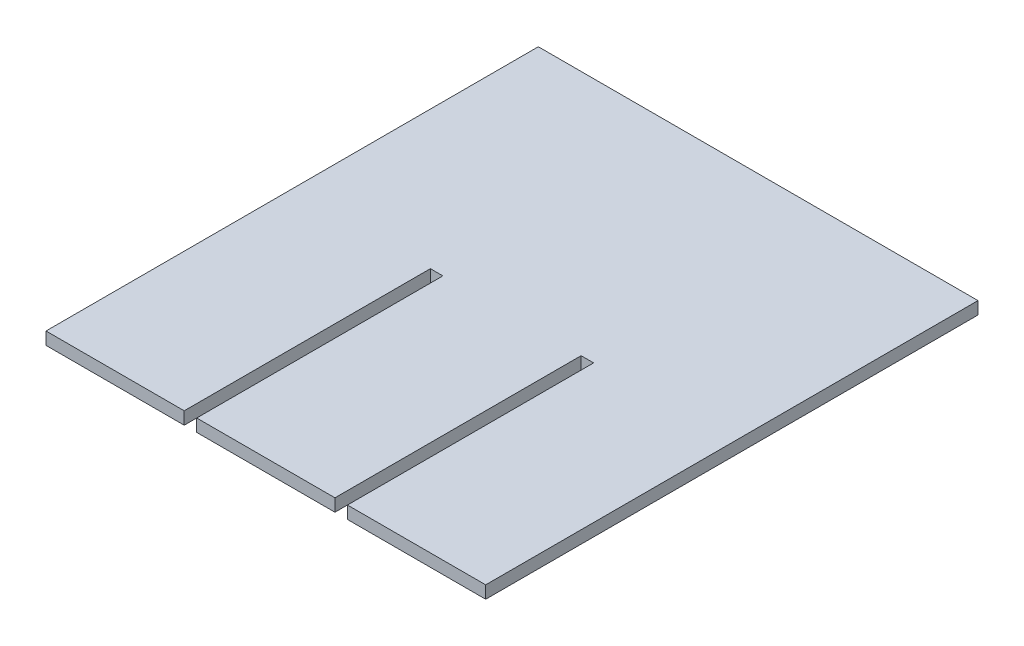
SolidWorks part; units mm, degrees
ref_plane "Front" through (0, 0, 0) normal (0, 0, 1) x (1, 0, 0)
ref_plane "Top" through (0, 0, 0) normal (0, 1, 0) x (1, 0, 0)
ref_plane "Right" through (0, 0, 0) normal (1, 0, 0) x (0, 0, -1)
sketch "Sketch1" plane through (0, 0, 0) normal (0, 1, 0) x (1, 0, 0)
  line L0 (0, 187.5) -> (105.2833, 187.5) construction
  line L1 (0, 0) -> (334.9, 0)
  line L2 (0, 0) -> (0, 375)
  line L3 (0, 375) -> (334.9, 375)
  line L4 (334.9, 0) -> (334.9, 375)
  line L5 (105.2833, 187.5) -> (114.8083, 187.5) construction
  line L6 (114.8083, 187.5) -> (220.0917, 187.5) construction
  line L7 (220.0917, 187.5) -> (229.6167, 187.5) construction
  line L8 (229.6167, 187.5) -> (334.9, 187.5) construction
  line L9 (105.2833, 0) -> (105.2833, 187.5)
  line L10 (105.2833, 187.5) -> (114.8083, 187.5)
  line L11 (114.8083, 187.5) -> (114.8083, 0)
  line L12 (220.0917, 0) -> (220.0917, 187.5)
  line L13 (229.6167, 187.5) -> (229.6167, 0)
  line L14 (229.6167, 187.5) -> (220.0917, 187.5)
  dimension "D1" = 334.9
  dimension "D2" = 375
  dimension "D3" = 9.525
extrude "Boss-Extrude1" add sketch "Sketch1" along normal blind 9.525 contours L14 L13 L1 L4 L3 L2 L9 L10 L11 L12
